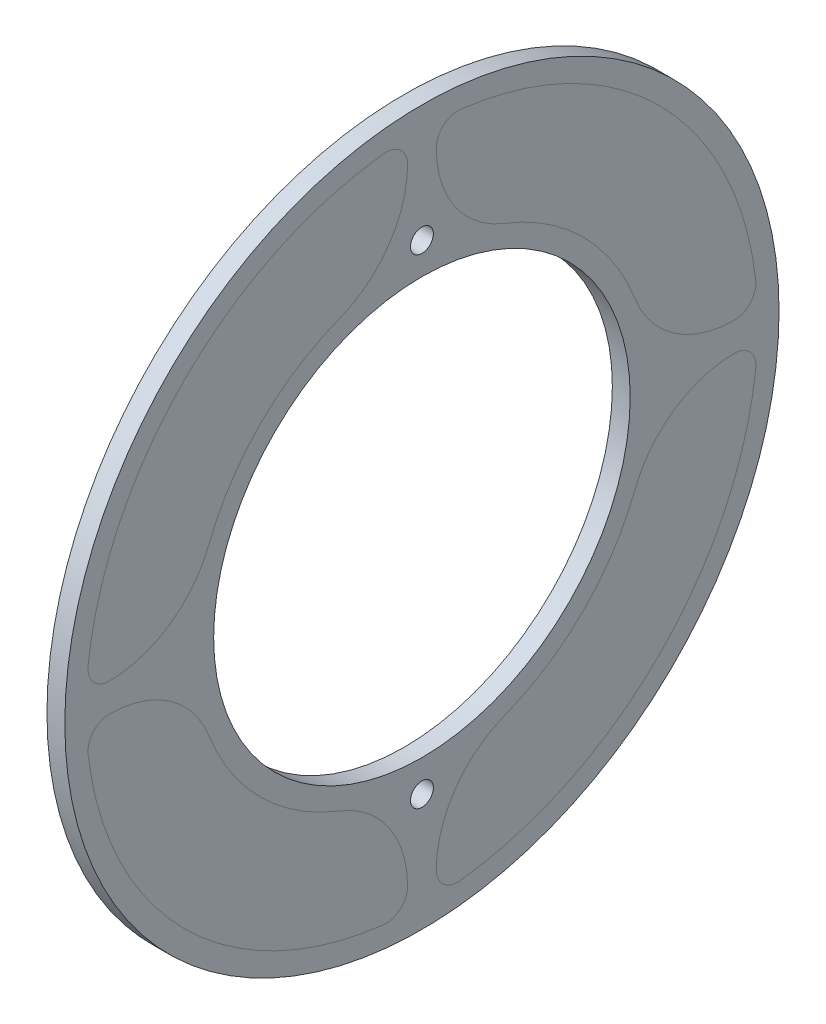
SolidWorks part; units mm, degrees
ref_plane "Front Plane" through (0, 0, 0) normal (0, 0, 1) x (1, 0, 0)
ref_plane "Top Plane" through (0, 0, 0) normal (0, 1, 0) x (1, 0, 0)
ref_plane "Right Plane" through (0, 0, 0) normal (1, 0, 0) x (0, 0, -1)
sketch "Sketch1" plane through (0, 0, 0) normal (1, 0, 0) x (0, 0, -1)
  circle A0 centre (0, 0) radius 29.16
  circle A1 centre (0, 0) radius 33.58 construction
  circle A2 centre (0, 0) radius 50
  circle A3 centre (0, 33.58) radius 1.6
  circle A4 centre (0, -33.58) radius 1.6
  dimension "D1" = 58.32
  dimension "D2" = 67.16
  dimension "D3" = 100
  dimension "D4" = 3.2
extrude "Boss-Extrude1" add sketch "Sketch1" along normal blind 2.5
sketch "Sketch2" plane through (2.5, 0, 0) normal (1, 0, 0) x (0, 0, -1)
  line L0 (32, 0) -> (47, 0) construction
  line L1 (32, -2) -> (47, -2) construction
  line L2 (43.8178, 2) -> (47, 2)
  line L3 (2, 43.8178) -> (2, 47)
  line L4 (32, 2) -> (47, 2) construction
  line L5 (43.8178, -2) -> (47, -2)
  line L6 (2, -43.8178) -> (2, -47)
  line L7 (-2, -43.8178) -> (-2, -47)
  line L8 (-43.8178, -2) -> (-47, -2)
  line L9 (-43.8178, 2) -> (-47, 2)
  line L10 (-2, 43.8178) -> (-2, 47)
  arc A0 (2, -47) -> (47, -2) centre (0, 0) ccw
  arc A1 (2, -43.8178) -> (11.5745, -29.8334) centre (17, -43.8178) cw
  arc A2 (11.5745, -29.8334) -> (29.8334, -11.5745) centre (0, 0) ccw
  arc A3 (29.8334, -11.5745) -> (43.8178, -2) centre (43.8178, -17) cw
  arc A4 (-47, -2) -> (-2, -47) centre (0, 0) ccw
  arc A5 (29.8334, 11.5745) -> (11.5745, 29.8334) centre (0, 0) ccw
  arc A6 (47, 2) -> (2, 47) centre (0, 0) ccw
  arc A7 (43.8178, 2) -> (29.8334, 11.5745) centre (43.8178, 17) cw
  arc A8 (11.5745, 29.8334) -> (2, 43.8178) centre (17, 43.8178) cw
  arc A9 (-43.8178, -2) -> (-29.8334, -11.5745) centre (-43.8178, -17) cw
  arc A10 (-29.8334, -11.5745) -> (-11.5745, -29.8334) centre (0, 0) ccw
  arc A11 (-11.5745, -29.8334) -> (-2, -43.8178) centre (-17, -43.8178) cw
  arc A12 (-2, 47) -> (-47, 2) centre (0, 0) ccw
  arc A13 (-2, 43.8178) -> (-11.5745, 29.8334) centre (-17, 43.8178) cw
  arc A14 (-11.5745, 29.8334) -> (-29.8334, 11.5745) centre (0, 0) ccw
  arc A15 (-29.8334, 11.5745) -> (-43.8178, 2) centre (-43.8178, 17) cw
  point P12 (0, 0)
  point P43 (0, 0)
  dimension "D2" = 32
  dimension "D6" = 15
  dimension "D7" = 32
  dimension "D1" = 15
  dimension "D3" = 2
  dimension "D4" = 2
  dimension "D5" = 2
  dimension "D8" = 4
extrude "Cut-Extrude1" cut sketch "Sketch2" against normal blind 21.84
fillet "Fillet1" radius 3 8 edges at (1.25, 2, 47) (1.25, -2, 47) (1.25, -47, 2) (1.25, -47, -2) (1.25, -2, -47) (1.25, 2, -47) (1.25, 47, -2) (1.25, 47, 2)
sketch "Sketch3" plane through (2.5, 0, 0) normal (1, 0, 0) x (0, 0, -1)
  arc A4 (46.7384, 5.3407) -> (5.3407, 46.7384) centre (0, 0) ccw
  arc A5 (29.8334, 11.5745) -> (43.7428, 2.0002) centre (43.8178, 17) ccw
  arc A6 (29.8334, 11.5745) -> (11.5745, 29.8334) centre (0, 0) ccw
  arc A7 (2.0002, 43.7428) -> (11.5745, 29.8334) centre (17, 43.8178) ccw
  arc A9 (29.8334, 11.5745) -> (43.7428, 2.0002) centre (43.8178, 17) ccw
  arc A10 (29.8334, 11.5745) -> (11.5745, 29.8334) centre (0, 0) ccw
  arc A11 (2.0002, 43.7428) -> (11.5745, 29.8334) centre (17, 43.8178) ccw
  arc A12 (5.3407, -46.7384) -> (46.7384, -5.3407) centre (0, 0) ccw
  arc A13 (11.5745, -29.8334) -> (2.0002, -43.7428) centre (17, -43.8178) ccw
  arc A14 (11.5745, -29.8334) -> (29.8334, -11.5745) centre (0, 0) ccw
  arc A15 (43.7428, -2.0002) -> (29.8334, -11.5745) centre (43.8178, -17) ccw
  arc A17 (11.5745, -29.8334) -> (2.0002, -43.7428) centre (17, -43.8178) ccw
  arc A18 (11.5745, -29.8334) -> (29.8334, -11.5745) centre (0, 0) ccw
  arc A19 (43.7428, -2.0002) -> (29.8334, -11.5745) centre (43.8178, -17) ccw
  arc A20 (-46.7384, -5.3407) -> (-5.3407, -46.7384) centre (0, 0) ccw
  arc A21 (-29.8334, -11.5745) -> (-43.7428, -2.0002) centre (-43.8178, -17) ccw
  arc A22 (-29.8334, -11.5745) -> (-11.5745, -29.8334) centre (0, 0) ccw
  arc A23 (-2.0002, -43.7428) -> (-11.5745, -29.8334) centre (-17, -43.8178) ccw
  arc A25 (-29.8334, -11.5745) -> (-43.7428, -2.0002) centre (-43.8178, -17) ccw
  arc A26 (-29.8334, -11.5745) -> (-11.5745, -29.8334) centre (0, 0) ccw
  arc A27 (-2.0002, -43.7428) -> (-11.5745, -29.8334) centre (-17, -43.8178) ccw
  arc A28 (-5.3407, 46.7384) -> (-46.7384, 5.3407) centre (0, 0) ccw
  arc A29 (-11.5745, 29.8334) -> (-2.0002, 43.7428) centre (-17, 43.8178) ccw
  arc A30 (-11.5745, 29.8334) -> (-29.8334, 11.5745) centre (0, 0) ccw
  arc A31 (-43.7428, 2.0002) -> (-29.8334, 11.5745) centre (-43.8178, 17) ccw
  arc A33 (-11.5745, 29.8334) -> (-2.0002, 43.7428) centre (-17, 43.8178) ccw
  arc A34 (-11.5745, 29.8334) -> (-29.8334, 11.5745) centre (0, 0) ccw
  arc A35 (-43.7428, 2.0002) -> (-29.8334, 11.5745) centre (-43.8178, 17) ccw
  arc A36 (46.7384, 5.3407) -> (5.3407, 46.7384) centre (0, 0) ccw
  arc A37 (5.3407, -46.7384) -> (46.7384, -5.3407) centre (0, 0) ccw
  arc A38 (-46.7384, -5.3407) -> (-5.3407, -46.7384) centre (0, 0) ccw
  arc A39 (-5.3407, 46.7384) -> (-46.7384, 5.3407) centre (0, 0) ccw
  arc A42 (43.7428, 2.0002) -> (46.7384, 5.3407) centre (43.7578, 5.0002) ccw
  arc A43 (43.7428, 2.0002) -> (46.7384, 5.3407) centre (43.7578, 5.0002) ccw
  arc A44 (5.3407, 46.7384) -> (2.0002, 43.7428) centre (5.0002, 43.7578) ccw
  arc A45 (5.3407, 46.7384) -> (2.0002, 43.7428) centre (5.0002, 43.7578) ccw
  arc A46 (2.0002, -43.7428) -> (5.3407, -46.7384) centre (5.0002, -43.7578) ccw
  arc A47 (2.0002, -43.7428) -> (5.3407, -46.7384) centre (5.0002, -43.7578) ccw
  arc A48 (46.7384, -5.3407) -> (43.7428, -2.0002) centre (43.7578, -5.0002) ccw
  arc A49 (46.7384, -5.3407) -> (43.7428, -2.0002) centre (43.7578, -5.0002) ccw
  arc A50 (-43.7428, -2.0002) -> (-46.7384, -5.3407) centre (-43.7578, -5.0002) ccw
  arc A51 (-43.7428, -2.0002) -> (-46.7384, -5.3407) centre (-43.7578, -5.0002) ccw
  arc A52 (-5.3407, -46.7384) -> (-2.0002, -43.7428) centre (-5.0002, -43.7578) ccw
  arc A53 (-5.3407, -46.7384) -> (-2.0002, -43.7428) centre (-5.0002, -43.7578) ccw
  arc A54 (-2.0002, 43.7428) -> (-5.3407, 46.7384) centre (-5.0002, 43.7578) ccw
  arc A55 (-2.0002, 43.7428) -> (-5.3407, 46.7384) centre (-5.0002, 43.7578) ccw
  arc A56 (-46.7384, 5.3407) -> (-43.7428, 2.0002) centre (-43.7578, 5.0002) ccw
  arc A57 (-46.7384, 5.3407) -> (-43.7428, 2.0002) centre (-43.7578, 5.0002) ccw
  dimension "D1" = 0
  dimension "D2" = 0
  dimension "D3" = 0
  dimension "D4" = 0
extrude "Boss-Extrude2" add sketch "Sketch3" against normal blind 2.5 separate body
